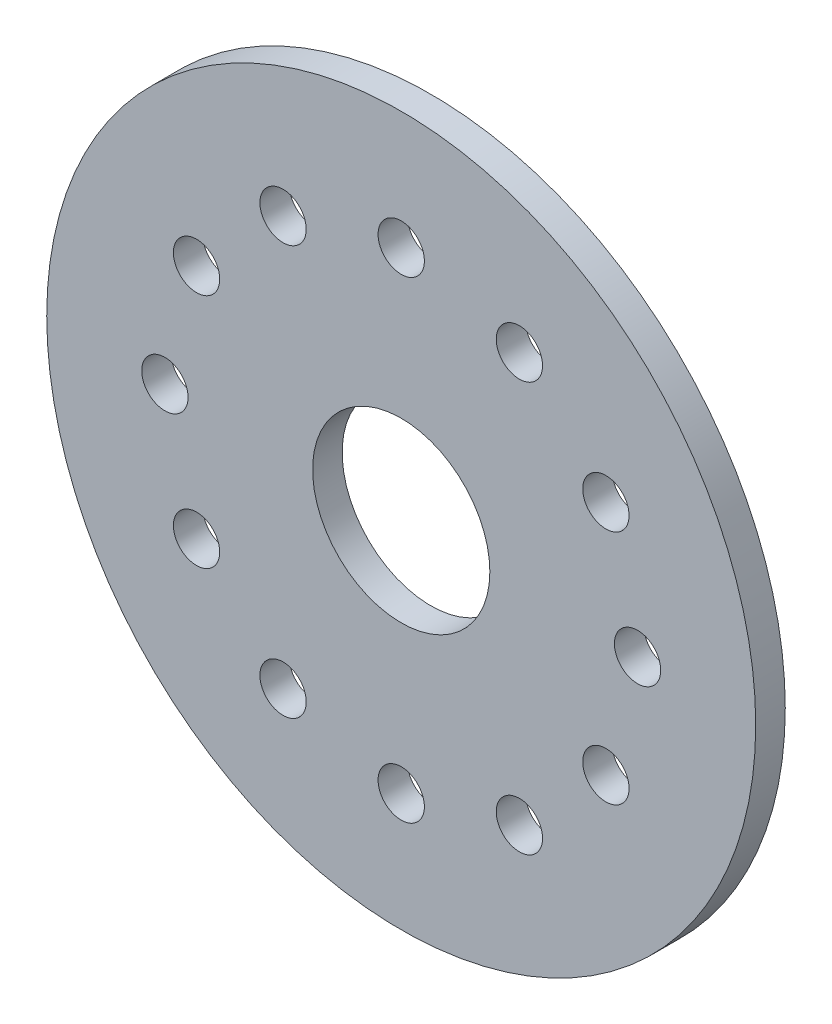
SolidWorks part; units mm, degrees
material "PC High Viscosity"
ref_plane "Front Plane" through (0, 0, 0) normal (0, 0, 1) x (1, 0, 0)
ref_plane "Top Plane" through (0, 0, 0) normal (0, 1, 0) x (1, 0, 0)
ref_plane "Right Plane" through (0, 0, 0) normal (1, 0, 0) x (0, 0, -1)
sketch "Sketch1" plane through (0, 0, 0) normal (0, 0, 1) x (1, 0, 0)
  circle A0 centre (0, 0) radius 9.525
  circle A1 centre (0, 0) radius 38.1
  circle A2 centre (0, 25.4) radius 2.4892
  circle A3 centre (12.7, 21.997) radius 2.4892
  circle A4 centre (21.997, 12.7) radius 2.4892
  circle A5 centre (25.4, 0) radius 2.4892
  circle A6 centre (21.997, -12.7) radius 2.4892
  circle A7 centre (12.7, -21.997) radius 2.4892
  circle A8 centre (0, -25.4) radius 2.4892
  circle A9 centre (-12.7, -21.997) radius 2.4892
  circle A10 centre (-21.997, -12.7) radius 2.4892
  circle A11 centre (-25.4, 0) radius 2.4892
  circle A12 centre (-21.997, 12.7) radius 2.4892
  circle A13 centre (-12.7, 21.997) radius 2.4892
  circle A14 centre (0, 0) radius 25.4 construction
  point P30 (0, 0)
  dimension "D1" = 19.05
  dimension "D2" = 25.4
  dimension "D3" = 4.9784
  dimension "D5" = 12.7
  dimension "D4" = 12
extrude "Boss-Extrude1" add sketch "Sketch1" along normal blind 3.175
